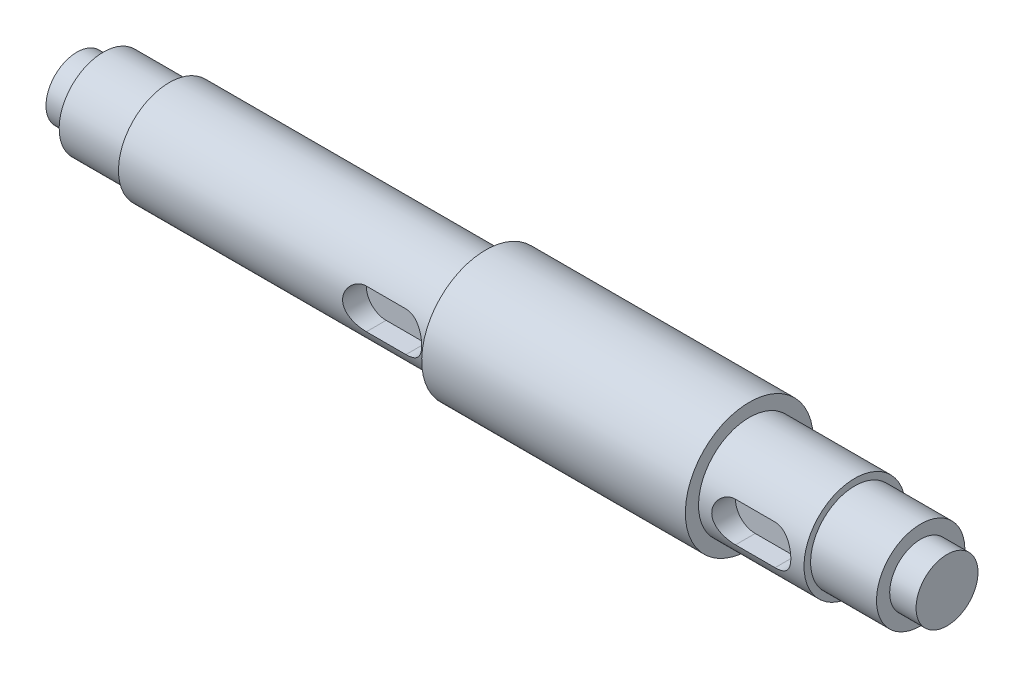
SolidWorks part; units mm, degrees
ref_plane "前视基准面" through (0, 0, 0) normal (0, 0, 1) x (1, 0, 0)
ref_plane "上视基准面" through (0, 0, 0) normal (0, 1, 0) x (1, 0, 0)
ref_plane "右视基准面" through (0, 0, 0) normal (1, 0, 0) x (0, 0, -1)
other "Configuration Table"
sketch "草图1" plane through (0, 0, 0) normal (0, 0, 1) x (1, 0, 0)
  line L0 (0, 0) -> (0, 2.35)
  line L1 (0, 2.35) -> (2, 2.35)
  line L2 (2, 2.35) -> (2, 3.35)
  line L3 (2, 3.35) -> (7, 3.35)
  line L4 (7, 3.35) -> (7, 3.85)
  line L5 (7, 3.85) -> (31, 3.85)
  line L6 (33, 3.85) -> (33, -28.86) construction
  line L7 (59, 3.35) -> (59, 3.85)
  line L8 (64, 3.35) -> (59, 3.35)
  line L9 (64, 2.35) -> (64, 3.35)
  line L10 (66, 2.35) -> (64, 2.35)
  line L11 (66, 0) -> (66, 2.35)
  line L12 (0, 0) -> (66, 0) construction
  line L13 (0, 0) -> (66, 0)
  line L16 (31, 4.85) -> (31, 3.85)
  line L17 (51, 4.85) -> (51, 3.85)
  line L18 (31, 4.85) -> (51, 4.85)
  line L19 (51, 3.85) -> (59, 3.85)
  dimension "D1" = 2.35
  dimension "D2" = 1
  dimension "D3" = 0.5
  dimension "D4" = 2
  dimension "D5" = 5
  dimension "D6" = 52
  dimension "D7" = 20
  dimension "D8" = 8
  dimension "D9" = 24
  dimension "D11" = 1
  dimension "D12" = 1
revolve "旋转1" add sketch "草图1" angle 360 about L13
ref_plane "基准面1" through (0, 0, 3.85) normal (0, 0, 1) x (1, 0, 0)
sketch "草图2" plane through (0, 0, 3.85) normal (0, 0, 1) x (1, 0, 0)
  line L0 (25.5, 0) -> (28.5, 0) construction
  line L1 (25.5, 1.5) -> (28.5, 1.5)
  line L2 (25.5, -1.5) -> (28.5, -1.5)
  line L3 (53.5, 0) -> (56.5, 0) construction
  line L4 (53.5, 1.5) -> (56.5, 1.5)
  line L5 (53.5, -1.5) -> (56.5, -1.5)
  line L6 (31, 4.85) -> (31, -4.85) construction
  line L7 (51, -4.85) -> (51, 4.85) construction
  line L8 (7, 3.85) -> (7, -3.85) construction
  line L9 (7, 3.35) -> (7, -3.35) construction
  arc A0 (25.5, 1.5) -> (25.5, -1.5) centre (25.5, 0) ccw
  arc A1 (28.5, -1.5) -> (28.5, 1.5) centre (28.5, 0) ccw
  arc A2 (53.5, 1.5) -> (53.5, -1.5) centre (53.5, 0) ccw
  arc A3 (56.5, -1.5) -> (56.5, 1.5) centre (56.5, 0) ccw
  point P3 (27, 0)
  point P8 (55, 0)
  dimension "D1" = 1.5
  dimension "D8" = 1.5
  dimension "D2" = 3
  dimension "D3" = 4
  dimension "D4" = 3
  dimension "D5" = 4
  dimension "D6" = 20
  dimension "D7" = 20
extrude "切除-拉伸1" cut sketch "草图2" against normal blind 1.8
